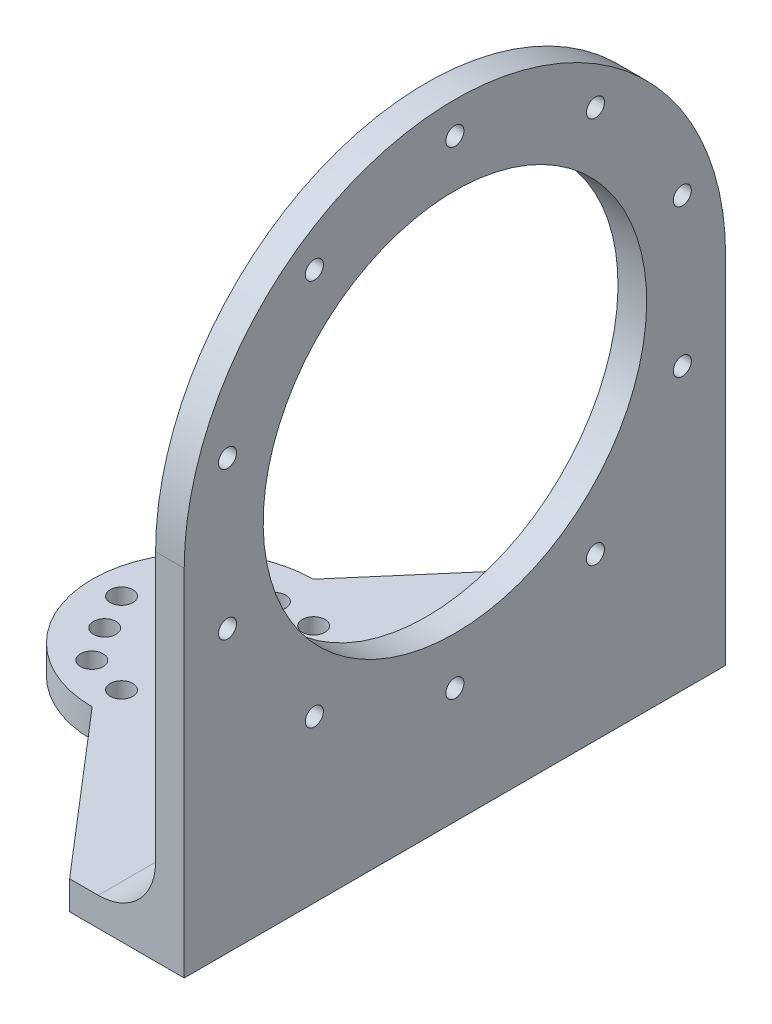
SolidWorks part; units mm, degrees
material "6061 Alloy"
ref_plane "Front Plane" through (0, 0, 0) normal (0, 0, 1) x (1, 0, 0)
ref_plane "Top Plane" through (0, 0, 0) normal (0, 1, 0) x (1, 0, 0)
ref_plane "Right Plane" through (0, 0, 0) normal (1, 0, 0) x (0, 0, -1)
sketch "Sketch0" plane through (0, 0, 0) normal (0, 0, 1) x (1, 0, 0)
  line L0 (-50.8, -76.2) -> (50.8, -76.2)
  line L1 (50.8, -76.2) -> (50.8, 76.2)
  line L2 (50.8, 0) -> (0, 0) construction
  line L3 (0, 0) -> (0, -76.2) construction
  line L4 (44.45, -57.15) -> (44.45, 76.2) construction
  line L5 (31.75, -69.85) -> (-50.8, -69.85) construction
  arc A0 (44.45, -57.15) -> (31.75, -69.85) centre (31.75, -57.15) cw
  point P3 (40.7303, -66.1303)
  dimension "Inside Corner Radius" = 12.7
  dimension "Outside Height" = 152.4
  dimension "Inside Height" = 146.05
  dimension "Inside Width" = 95.25
  dimension "Wall Thickness" = 6.35
  dimension "D1" = 6.35
  dimension "Outside Width" = 101.6
sketch "Sketch1" plane through (0, 0, 0) normal (1, 0, 0) x (0, 0, -1)
  line L0 (152.4, 0) -> (-152.4, 0)
  point P4 (0, 0)
  dimension "Length" = 304.8
sketch "Sketch2" plane through (0, 0, 0) normal (0, 0, 1) x (1, 0, 0)
  line L0 (-50.8, -76.2) -> (50.8, -76.2)
  line L1 (50.8, -76.2) -> (50.8, 76.2)
  line L2 (50.8, 76.2) -> (44.45, 76.2) construction
  line L3 (44.45, 73.025) -> (44.45, -57.15)
  line L4 (31.75, -69.85) -> (-47.625, -69.85)
  line L5 (-50.8, -76.2) -> (-50.8, -69.85) construction
  line L6 (47.625, 76.2) -> (50.8, 76.2)
  line L7 (-50.8, -73.025) -> (-50.8, -76.2)
  line L8 (50.8, 0) -> (0, 0) construction
  line L9 (0, 0) -> (0, -76.2) construction
  arc A0 (44.45, 73.025) -> (47.625, 76.2) centre (47.625, 73.025) cw
  arc A1 (-50.8, -73.025) -> (-47.625, -69.85) centre (-47.625, -73.025) cw
  arc A2 (44.45, -57.15) -> (31.75, -69.85) centre (31.75, -57.15) cw
  dimension "Inside Radius" = 12.7
  dimension "Height" = 152.4
  dimension "Width" = 101.6
  dimension "Thickness" = 6.35
extrude "Boss-Extrude1" add sketch "Sketch2" along normal blind 120
sketch "Break Locations" plane through (0, 0, 0) normal (1, 0, 0) x (0, 0, -1)
  line L0 (155.448, 0) -> (-155.448, 0)
  line L1 (-120, -76.2) -> (-120, 76.2) construction
  line L2 (0, -76.2) -> (0, 76.2) construction
  point P0 (9.54, 0)
  point P1 (-129.54, 0)
  point P10 (0, 0)
  point P11 (-155.448, 0)
  point P13 (155.448, 0)
  dimension "D1" = 129.54
  dimension "D2" = 129.54
  dimension "D3" = 155.448
sketch "Sketch3" plane through (0, -69.85, 0) normal (0, 1, 0) x (1, 0, 0)
  line L6 (31.75, 0) -> (-47.625, 0) construction
  line L9 (-5.1, -35.5) -> (25.4, 0)
  line L11 (31.75, -120) -> (-47.625, -120) construction
  line L12 (25.4, -120) -> (-5.1, -84.5)
  line L13 (25.4, 0) -> (-50.8, 0)
  line L14 (-50.8, 0) -> (-50.8, -120)
  line L15 (-50.8, -120) -> (25.4, -120)
  arc A1 (-5.1, -35.5) -> (-5.1, -84.5) centre (-5.1, -60) ccw
extrude "Cut-Extrude1" cut sketch "Sketch3" against normal up to surface (6.35 mm away) up to face at (0, -76.2, 60)
sketch "Sketch4" plane through (0, -69.85, 0) normal (0, 1, 0) x (1, 0, 0)
  circle A0 centre (-5.1, -60) radius 24.5 construction
  circle A1 centre (-5.1, -60) radius 18 construction
  circle A2 centre (-5.1, -60) radius 15.9 construction
  circle A3 centre (-5.1, -44.1) radius 2.5
  circle A4 centre (8.6698, -67.95) radius 2.5
  circle A5 centre (-18.8698, -67.95) radius 2.5
  circle A6 centre (3.9, -44.4115) radius 2.5
  circle A7 centre (10.4885, -51) radius 2.5
  circle A8 centre (12.9, -60) radius 2.5
  circle A9 centre (3.9, -75.5885) radius 2.5
  circle A10 centre (-5.1, -78) radius 2.5
  circle A11 centre (-14.1, -75.5885) radius 2.5
  circle A12 centre (-23.1, -60) radius 2.5
  circle A13 centre (-20.6885, -51) radius 2.5
  circle A14 centre (-14.1, -44.4115) radius 2.5
  point P12 (-5.1, -60)
  point P17 (-5.1, -60)
  point P30 (-5.1, -60)
extrude "Cut-Extrude2" cut sketch "Sketch4" against normal up to surface (6.35 mm away) up to face at (19.6167, -76.2, 60)
sketch "Sketch5" plane through (44.45, 0, 0) normal (-1, 0, 0) x (0, 0, 1)
  circle A3 centre (60, 55.45) radius 2
  circle A4 centre (91.1526, 45.3279) radius 2
  circle A5 centre (110.406, 18.8279) radius 2
  circle A6 centre (110.406, -13.9279) radius 2
  circle A7 centre (91.1526, -40.4279) radius 2
  circle A8 centre (60, -50.55) radius 2
  circle A9 centre (28.8474, -40.4279) radius 2
  circle A10 centre (9.594, -13.9279) radius 2
  circle A11 centre (9.594, 18.8279) radius 2
  circle A12 centre (28.8474, 45.3279) radius 2
  circle A13 centre (60, 2.45) radius 42.5
  point P38 (60, 2.45)
  dimension "D2" = 85
  dimension "D3" = 4
extrude "Cut-Extrude4" cut sketch "Sketch5" against normal up to surface (6.35 mm away) up to face at (50.8, 0, 60)
sketch "Sketch6" plane through (44.45, 0, 0) normal (-1, 0, 0) x (0, 0, 1)
  line L3 (0, 76.2) -> (0, 2.45)
  line L5 (120, 2.45) -> (120, 76.2)
  line L6 (120, 73.025) -> (120, 76.2) construction
  line L7 (120, 76.2) -> (0, 76.2) construction
  line L8 (120, 76.2) -> (0, 76.2)
  arc A0 (120, 2.45) -> (0, 2.45) centre (60, 2.45) ccw
extrude "Cut-Extrude8" cut sketch "Sketch6" against normal up to surface (6.35 mm away) up to face at (50.8, -15.9279, 9.594)
sketch "Sketch7" plane through (0, -69.85, 0) normal (0, 1, 0) x (1, 0, 0)
  line L0 (12.9, -60) -> (31.75, -60)
  line L1 (31.75, -120) -> (31.75, 0) construction
equation "\"D1@Break Locations\" = .85 * \"Height@Sketch2\""
equation "\"D2@Break Locations\"=\"D1@Break Locations\""
equation "\"Thickness@Sketch2\"=\"wall thickness@sketch0\""
equation "\"Height@Sketch2\"=\"outside height@sketch0\""
equation "\"Width@Sketch2\"=\"outside width@sketch0\""
equation "\"Inside Radius@Sketch2\"=\"inside corner radius@sketch0\""
equation "\"D3@Break Locations\"=\"D2@Break Locations\"*1.2"
equation "\"D1@Sketch0\"=\"Wall Thickness@Sketch0\""
